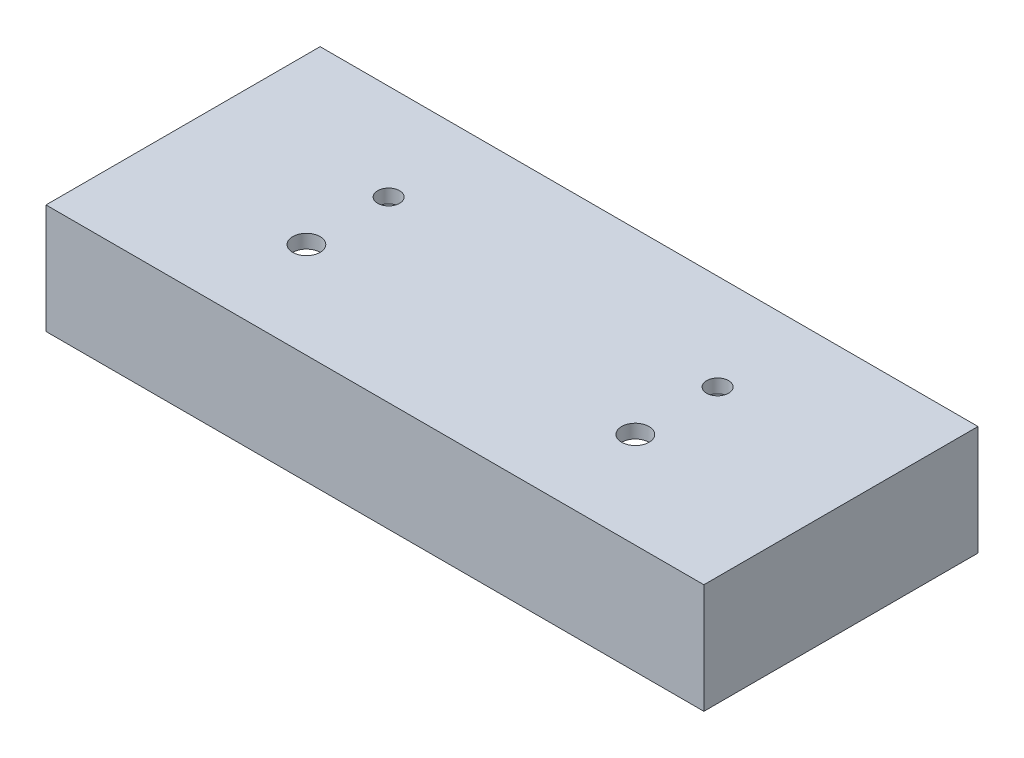
SolidWorks part; units mm, degrees
ref_plane "Front Plane" through (0, 0, 0) normal (0, 0, 1) x (1, 0, 0)
ref_plane "Top Plane" through (0, 0, 0) normal (0, 1, 0) x (1, 0, 0)
ref_plane "Right Plane" through (0, 0, 0) normal (1, 0, 0) x (0, 0, -1)
sketch "Sketch1" plane through (0, 0, 0) normal (0, 1, 0) x (1, 0, 0)
  line L1 (-152.4, -63.5) -> (152.4, -63.5)
  line L2 (-152.4, -63.5) -> (-152.4, 63.5)
  line L3 (-152.4, 63.5) -> (152.4, 63.5)
  line L4 (152.4, -63.5) -> (152.4, 63.5)
  line L5 (-152.4, -63.5) -> (152.4, 63.5) construction
  line L6 (-152.4, 63.5) -> (152.4, -63.5) construction
  point P0 (0, 0)
  dimension "D1" = 127
  dimension "D2" = 304.8
extrude "Boss-Extrude1" add sketch "Sketch1" along normal blind 50.8
sketch "Sketch2" plane through (0, 0, 0) normal (0, -1, 0) x (1, 0, 0)
  line L0 (-152.4, -63.5) -> (-152.4, 63.5) construction
  line L1 (-139.7, 50.8) -> (139.7, 50.8)
  line L2 (-139.7, 50.8) -> (-139.7, -50.8)
  line L3 (-139.7, -50.8) -> (139.7, -50.8)
  line L4 (139.7, 50.8) -> (139.7, -50.8)
  line L5 (-139.7, 50.8) -> (139.7, -50.8) construction
  line L6 (-139.7, -50.8) -> (139.7, 50.8) construction
  line L7 (-152.4, 63.5) -> (152.4, 63.5) construction
  point P0 (0, 0)
  dimension "D1" = 12.7
  dimension "D2" = 12.7
  dimension "D3" = 101.6
extrude "Cut-Extrude1" cut sketch "Sketch2" against normal blind 44.45
sketch "Sketch3" plane through (0, 50.8, 0) normal (0, 1, 0) x (1, 0, 0)
  line L1 (-152.4, 63.5) -> (-152.4, -63.5) construction
  line L2 (152.4, -63.5) -> (152.4, 63.5) construction
  line L4 (152.4, 63.5) -> (-152.4, 63.5) construction
  circle A0 centre (-76.2, 19.05) radius 5.08
  circle A1 centre (76.2, 19.05) radius 5.08
  circle A2 centre (-76.2, -19.05) radius 6.35
  circle A3 centre (76.2, -19.05) radius 6.35
  dimension "D5" = 38.1
  dimension "D7" = 10.16
  dimension "D8" = 10.16
  dimension "D1" = 76.2
  dimension "D2" = 76.2
  dimension "D3" = 44.45
  dimension "D4" = 44.45
  dimension "D6" = 38.1
extrude "Cut-Extrude2" cut sketch "Sketch3" against normal blind 12.7
